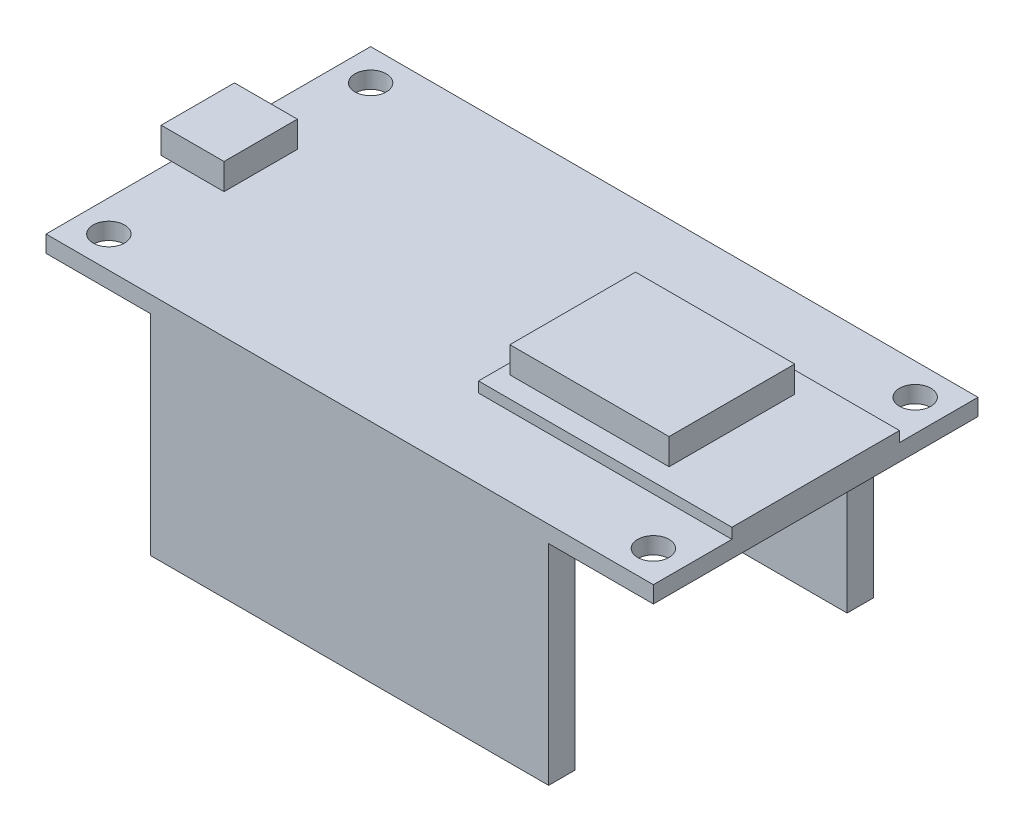
SolidWorks part; units mm, degrees
ref_plane "Front Plane" through (0, 0, 0) normal (0, 0, 1) x (1, 0, 0)
ref_plane "Top Plane" through (0, 0, 0) normal (0, 1, 0) x (1, 0, 0)
ref_plane "Right Plane" through (0, 0, 0) normal (1, 0, 0) x (0, 0, -1)
sketch "Sketch1" plane through (0, 0, 0) normal (0, 1, 0) x (1, 0, 0)
  line L1 (-29, -15.5) -> (29, -15.5)
  line L2 (-29, -15.5) -> (-29, 15.5)
  line L3 (-29, 15.5) -> (29, 15.5)
  line L4 (29, -15.5) -> (29, 15.5)
  line L5 (-29, -15.5) -> (29, 15.5) construction
  line L6 (-29, 15.5) -> (29, -15.5) construction
  point P0 (0, 0)
  point P5 (0, 0)
  dimension "D1" = 31
  dimension "D2" = 58
extrude "CIRCUIT" add sketch "Sketch1" along normal blind 1.6
sketch "Sketch2" plane through (0, 1.6, 0) normal (0, 1, 0) x (1, 0, 0)
  line L0 (29, -15.5) -> (29, 15.5) construction
  line L1 (29, 8) -> (4.8, 8)
  line L2 (29, 8) -> (29, -8)
  line L3 (29, -8) -> (4.8, -8)
  line L4 (4.8, 8) -> (4.8, -8)
  line L5 (29, 15.5) -> (-29, 15.5) construction
  dimension "D1" = 16
  dimension "D2" = 24.2
  dimension "D3" = 7.5
extrude "ESP_PCB" add sketch "Sketch2" along normal blind 1
sketch "Sketch3" plane through (0, 2.6, 0) normal (0, 1, 0) x (1, 0, 0)
  line L0 (29, -8) -> (29, 8) construction
  line L1 (5.8, 6) -> (21, 6)
  line L2 (5.8, 6) -> (5.8, -6)
  line L3 (5.8, -6) -> (21, -6)
  line L4 (21, 6) -> (21, -6)
  line L6 (4.8, 8) -> (4.8, -8) construction
  line L7 (29, 8) -> (4.8, 8) construction
  line L8 (4.8, -8) -> (29, -8) construction
  dimension "D1" = 8
  dimension "D2" = 1
  dimension "D3" = 2
  dimension "D4" = 2
extrude "ESP_CHIP" add sketch "Sketch3" along normal blind 2.5
sketch "Sketch4" plane through (0, 1.6, 0) normal (0, 1, 0) x (1, 0, 0)
  line L0 (-29, 15.5) -> (-29, -15.5) construction
  line L1 (-29, 3.5) -> (-24, 3.5)
  line L2 (-29, 3.5) -> (-29, -3.5)
  line L3 (-29, -3.5) -> (-24, -3.5)
  line L4 (-24, 3.5) -> (-24, -3.5)
  line L5 (29, 15.5) -> (-29, 15.5) construction
  line L6 (-29, -15.5) -> (29, -15.5) construction
  dimension "D1" = 5
  dimension "D2" = 12
  dimension "D3" = 12
extrude "PCB_HOLES" add sketch "Sketch4" along normal blind 2.5
sketch "Sketch5" plane through (0, 1.6, 0) normal (0, 1, 0) x (1, 0, 0)
  line L0 (29, 15.5) -> (-29, 15.5) construction
  line L1 (-29, 15.5) -> (-29, 3.5) construction
  line L3 (-29, -15.5) -> (29, -15.5) construction
  line L4 (29, 8) -> (29, 15.5) construction
  circle A0 centre (-26, 12.5) radius 1.5
  circle A1 centre (-26, -12.5) radius 1.5
  circle A2 centre (26, 12.5) radius 1.5
  circle A3 centre (26, -12.5) radius 1.5
  point P2 (0, 0)
  point P13 (0, 0)
  dimension "D1" = 3
  dimension "D2" = 3
  dimension "D3" = 3
  dimension "D4" = 3
  dimension "D5" = 3
extrude "Cut-Extrude1" cut sketch "Sketch5" against normal through all
sketch "Sketch6" plane through (-29, 0, 0) normal (-1, 0, 0) x (0, 0, 1)
  line L1 (-3.5, 4.1) -> (3.5, 4.1)
  line L2 (-3.5, 4.1) -> (-3.5, 1.6)
  line L3 (-3.5, 1.6) -> (3.5, 1.6)
  line L4 (3.5, 4.1) -> (3.5, 1.6)
extrude "USB" add sketch "Sketch6" along normal blind 1
sketch "Sketch7" plane through (0, 0, 0) normal (0, -1, 0) x (1, 0, 0)
  line L0 (-29, 15.5) -> (29, 15.5) construction
  line L1 (-19, 15.5) -> (19, 15.5)
  line L2 (-19, 15.5) -> (-19, 13)
  line L3 (-19, 13) -> (19, 13)
  line L4 (19, 15.5) -> (19, 13)
  line L5 (29, 15.5) -> (29, -15.5) construction
  line L6 (-29, -15.5) -> (-29, 15.5) construction
  line L7 (29, -15.5) -> (-29, -15.5) construction
  line L8 (-19, -15.5) -> (19, -15.5)
  line L9 (-19, -15.5) -> (-19, -13)
  line L10 (-19, -13) -> (19, -13)
  line L11 (19, -15.5) -> (19, -13)
  dimension "D1" = 2.5
  dimension "D2" = 10
  dimension "D3" = 10
  dimension "D4" = 10
  dimension "D5" = 10
  dimension "D6" = 2.5
extrude "PINS" add sketch "Sketch7" along normal blind 20
